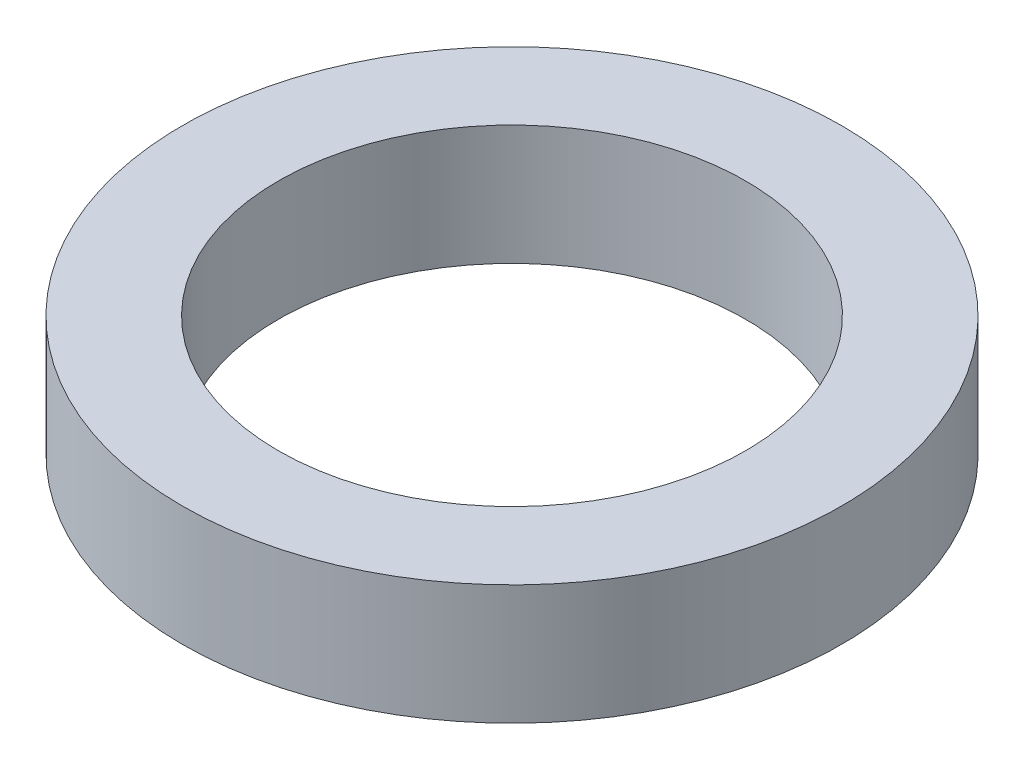
SolidWorks part; units mm, degrees
ref_plane "Front Plane" through (0, 0, 0) normal (0, 0, 1) x (1, 0, 0)
ref_plane "Top Plane" through (0, 0, 0) normal (0, 1, 0) x (1, 0, 0)
ref_plane "Right Plane" through (0, 0, 0) normal (1, 0, 0) x (0, 0, -1)
sketch "Sketch1" plane through (0, 0, 0) normal (0, 1, 0) x (1, 0, 0)
  circle A0 centre (0, 0) radius 1.9812
  circle A1 centre (0, 0) radius 2.794
  dimension "D1" = 3.9624
  dimension "D2" = 5.588
extrude "Boss-Extrude1" add sketch "Sketch1" along normal blind 1.016
